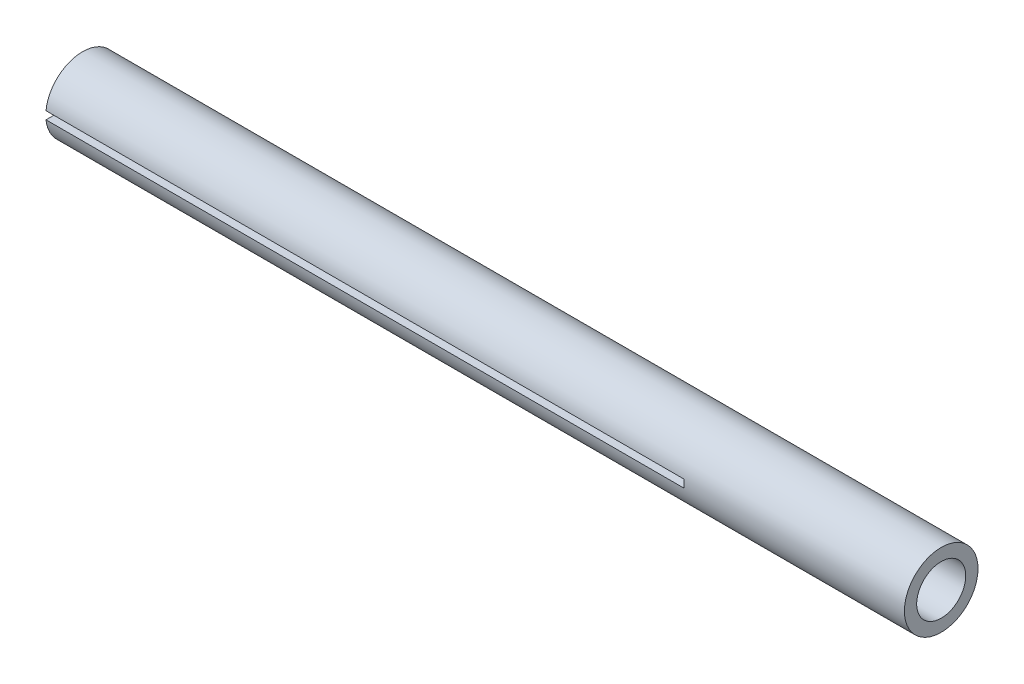
SolidWorks part; units mm, degrees
ref_plane "Front Plane" through (0, 0, 0) normal (0, 0, 1) x (1, 0, 0)
ref_plane "Top Plane" through (0, 0, 0) normal (0, 1, 0) x (1, 0, 0)
ref_plane "Right Plane" through (0, 0, 0) normal (1, 0, 0) x (0, 0, -1)
sketch "Sketch1" plane through (0, 0, 0) normal (1, 0, 0) x (0, 0, -1)
  circle A0 centre (-37.2908, 15.0495) radius 1.905
  circle A1 centre (-37.2908, 15.0495) radius 1.27
extrude "Boss-Extrude1" add sketch "Sketch1" along normal blind 44.45
ref_plane "Plane1" through (0, 0, 39.1958) normal (0, 0, 1) x (1, 0, 0)
sketch "Sketch2" plane through (0, 0, 39.1958) normal (0, 0, 1) x (1, 0, 0)
  line L1 (32.385, 15.1201) -> (33.02, 15.1201)
  line L10 (26.035, 15.1201) -> (31.75, 15.1201)
  line L12 (32.385, 15.1201) -> (31.75, 15.1201)
  line L15 (26.035, 15.1201) -> (25.4, 15.1201)
  line L16 (33.02, 15.1201) -> (33.02, 12.1991)
  line L17 (25.4, 15.1201) -> (25.4, 12.1991)
  line L18 (25.4, 12.1991) -> (33.02, 12.1991)
  line L19 (29.21, 12.1991) -> (27.305, 12.1991)
  line L20 (29.21, 12.1991) -> (31.194, 12.1991)
  dimension "D1" = 2.921
sketch "Sketch4" plane through (0, 0, 0) normal (-1, 0, 0) x (0, 0, 1)
  circle A0 centre (37.2908, 15.0495) radius 1.27
sketch "Sketch9" plane through (0, 0, 0) normal (-1, 0, 0) x (0, 0, 1)
  line L0 (37.2908, 15.0495) -> (39.1958, 15.0495)
  circle A0 centre (37.2908, 15.0495) radius 1.905 construction
sketch "Sketch10" plane through (0, 0, 39.1958) normal (0, 0, 1) x (1, 0, 0)
  line L2 (0, 15.0495) -> (0, 15.2527)
  line L3 (0, 15.2527) -> (33.0325, 15.2527)
  line L4 (33.0325, 15.0073) -> (33.0325, 15.2527)
  line L6 (0, 15.0495) -> (0, 14.8463)
  line L7 (0, 14.8463) -> (33.0325, 14.8463)
  line L8 (33.0325, 15.0073) -> (33.0325, 14.8463)
extrude "Cut-Extrude6" cut sketch "Sketch10" against normal blind 6.858 and the other way blind 8.382
sketch "Sketch12" plane through (44.45, 0, 0) normal (1, 0, 0) x (0, 0, -1)
  line L0 (-37.2908, 15.0495) -> (-39.1958, 15.0495)
  circle A0 centre (-37.2908, 15.0495) radius 1.905 construction
sketch "Sketch14" plane through (0, 0, 39.1958) normal (0, 0, 1) x (1, 0, 0)
  line L0 (44.45, 15.0495) -> (30.861, 15.0495)
